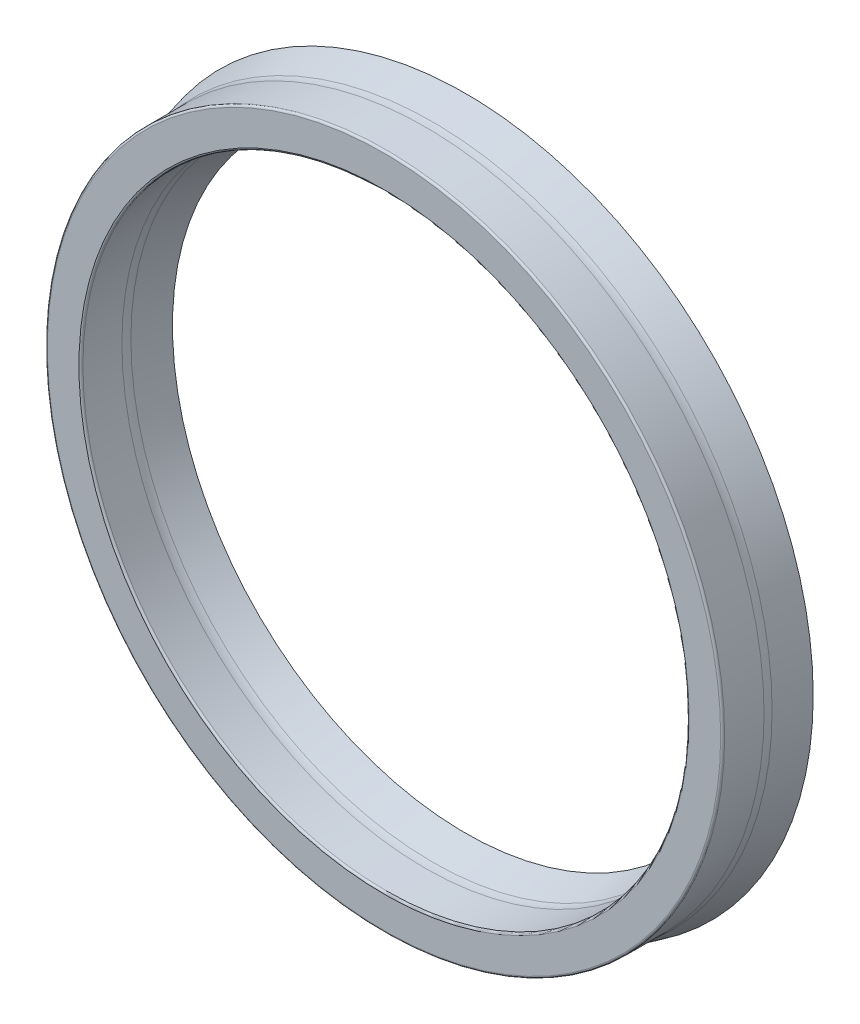
SolidWorks part; units mm, degrees
material "Nitrile Rubber"
ref_plane "Front Plane" through (0, 0, 0) normal (0, 0, 1) x (1, 0, 0)
ref_plane "Top Plane" through (0, 0, 0) normal (0, 1, 0) x (1, 0, 0)
ref_plane "Right Plane" through (0, 0, 0) normal (1, 0, 0) x (0, 0, -1)
sketch "Sketch1" plane through (0, 0, 0) normal (1, 0, 0) x (0, 0, -1)
  line L0 (0, 0) -> (20.282, 0) construction
  line L1 (0, 30.5) -> (0, 33.65)
  line L2 (0.2, 33.85) -> (4.1356, 33.85)
  line L3 (4.8538, 33.9372) -> (8.15, 34.75)
  line L4 (8.15, 34.75) -> (8.15, 33.5)
  line L5 (8.15, 33.5) -> (4.91, 32.555)
  line L7 (4.9238, 31.5912) -> (8.15, 30.75)
  line L8 (8.15, 30.75) -> (8.15, 29.3)
  line L9 (8.15, 29.3) -> (4.8892, 30.1934)
  line L10 (4.0965, 30.3) -> (0.2, 30.3)
  line L11 (0, 32.075) -> (8.8304, 32.075) construction
  arc A0 (4.91, 32.555) -> (4.9238, 31.5912) centre (5.05, 32.075) ccw
  arc A1 (0, 30.5) -> (0.2, 30.3) centre (0.2, 30.5) ccw
  arc A2 (0, 33.65) -> (0.2, 33.85) centre (0.2, 33.65) cw
  arc A3 (4.1356, 33.85) -> (4.8538, 33.9372) centre (4.1356, 36.85) ccw
  arc A4 (4.8892, 30.1934) -> (4.0965, 30.3) centre (4.0965, 27.3) ccw
  point P22 (4.5, 33.85)
  point P25 (4.5, 30.3)
  dimension "D8" = 0.5
  dimension "D10" = 0.2
  dimension "D11" = 3.6
  dimension "D13" = 3
  dimension "D1" = 8.15
  dimension "D2" = 4.5
  dimension "D3" = 4.5
  dimension "D4" = 67.7
  dimension "D5" = 60.6
  dimension "D6" = 69.5
  dimension "D7" = 58.6
  dimension "D9" = 61.5
  dimension "D12" = 67
revolve "Revolve1" add sketch "Sketch1" angle 360 about L0
